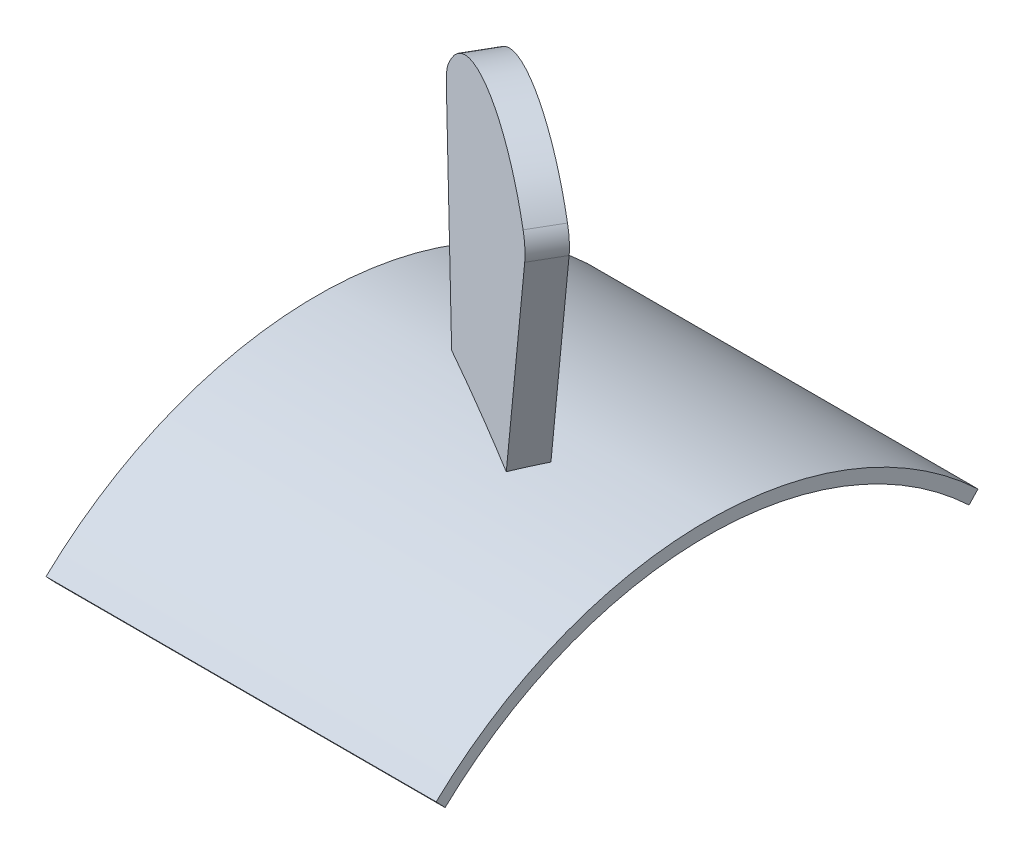
SolidWorks part; units mm, degrees
ref_plane "Front Plane" through (0, 0, 0) normal (0, 0, 1) x (1, 0, 0)
ref_plane "Top Plane" through (0, 0, 0) normal (0, 1, 0) x (1, 0, 0)
ref_plane "Right Plane" through (0, 0, 0) normal (1, 0, 0) x (0, 0, -1)
sketch "Sketch1" plane through (0, 0, 0) normal (1, 0, 0) x (0, 0, -1)
  arc A0 (-40.3747, 0) -> (65.4482, 0) centre (12.5367, -55.8968) cw
extrude "Extrude-Thin1" add sketch "Sketch1" against normal blind 76.2 thin
ref_plane "Plane1" through (0, 31.75, 0) normal (0, 1, 0) x (-1, 0, 0)
ref_plane "Plane2" through (-76.2, 21.0712, -12.5367) normal (0, 1, 0) x (-1, 0, 0)
sketch "Sketch5" plane through (-76.2, 21.0712, -12.5367) normal (0, 1, 0) x (-1, 0, 0)
  line L0 (-76.2, 0) -> (0, 0)
  line L1 (-76.2, 52.9115) -> (-76.2, -52.9115) construction
  line L2 (0, -52.9115) -> (0, 52.9115) construction
ref_plane "Plane3" through (0, 0, -12.5367) normal (0, 0, 1) x (1, 0, 0)
sketch "Sketch6" plane through (0, 0, -12.5367) normal (0, 0, 1) x (1, 0, 0)
  line L0 (-40.6067, 23.7979) -> (-40.6067, -5.3231)
ref_plane "Plane5" through (-4.7231, 0, 8.1807) normal (-0.5, 0, 0.866) x (0.866, 0, 0.5)
sketch "Sketch8" plane through (-4.7231, 0, 8.1807) normal (-0.5, 0, 0.866) x (0.866, 0, 0.5)
  line L0 (-26.0199, 19.3564) -> (-15.9602, 62.4698)
  line L1 (-54.8438, 19.3564) -> (-57.7818, 64.2616)
  line L2 (-54.8438, 19.3564) -> (-26.0199, 19.3564)
  arc A0 (-16.8213, 67.3755) -> (-56.5805, 68.4115) centre (-37.0575, 54.2105) ccw
  arc A1 (-16.8213, 67.3755) -> (-15.9602, 62.4698) centre (-22.1441, 63.9127) cw
  arc A2 (-57.7818, 64.2616) -> (-56.5805, 68.4115) centre (-51.4453, 64.6762) cw
  dimension "D1" = 6.35
extrude "Extrude3" add sketch "Sketch8" along normal mid plane 6.35
